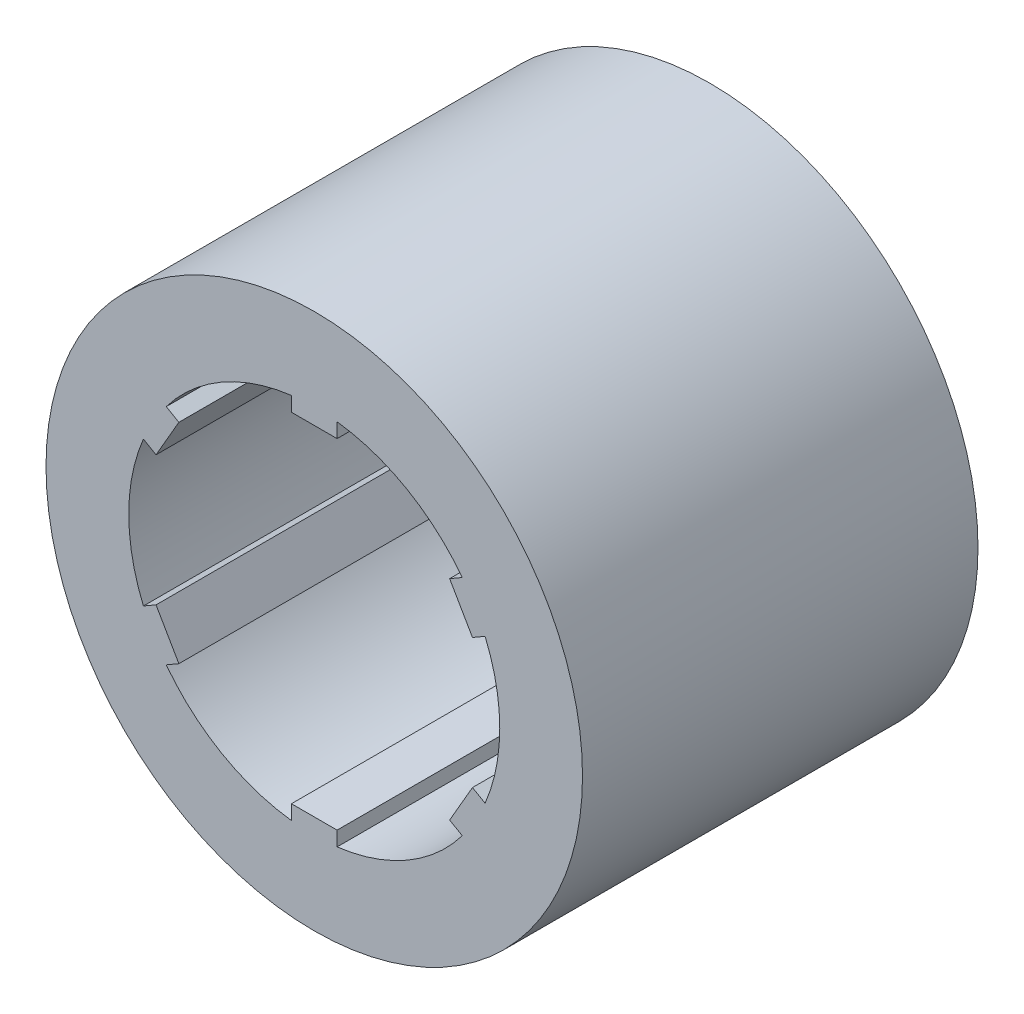
SolidWorks part; units mm, degrees
ref_plane "Спереди" through (0, 0, 0) normal (0, 0, 1) x (1, 0, 0)
ref_plane "Сверху" through (0, 0, 0) normal (0, 1, 0) x (1, 0, 0)
ref_plane "Справа" through (0, 0, 0) normal (1, 0, 0) x (0, 0, -1)
sketch "Эскиз1" plane through (0, 0, 0) normal (0, 0, 1) x (1, 0, 0)
  line L0 (9.0689, -4.0163) -> (9.7708, -4.4215)
  line L1 (9.7708, 3.6191) -> (9.0689, 3.2138)
  line L2 (9.0689, 3.2138) -> (7.7989, 5.4135)
  line L3 (7.7989, 5.4135) -> (8.5008, 5.8188)
  line L4 (1.5375, 9.8391) -> (1.5375, 9.0285)
  line L5 (1.5375, 9.0285) -> (-1.0025, 9.0285)
  line L6 (-1.0025, 9.0285) -> (-1.0025, 9.8391)
  line L7 (-7.9659, 5.8188) -> (-7.2639, 5.4135)
  line L8 (-7.2639, 5.4135) -> (-8.5339, 3.2138)
  line L9 (-8.5339, 3.2138) -> (-9.2359, 3.6191)
  line L10 (-9.2359, -4.4215) -> (-8.5339, -4.0163)
  line L11 (-8.5339, -4.0163) -> (-7.2639, -6.216)
  line L12 (-7.2639, -6.216) -> (-7.9659, -6.6212)
  line L13 (-1.0025, -10.6415) -> (-1.0025, -9.831)
  line L14 (-1.0025, -9.831) -> (1.5375, -9.831)
  line L15 (1.5375, -9.831) -> (1.5375, -10.6415)
  line L16 (8.5008, -6.6212) -> (7.7989, -6.216)
  line L17 (7.7989, -6.216) -> (9.0689, -4.0163)
  circle A0 centre (0.2675, -0.4012) radius 14.9225
  arc A1 (9.7708, -4.4215) -> (9.7708, 3.6191) centre (0.2675, -0.4012) ccw
  arc A2 (8.5008, 5.8188) -> (1.5375, 9.8391) centre (0.2675, -0.4012) ccw
  arc A3 (-1.0025, 9.8391) -> (-7.9659, 5.8188) centre (0.2675, -0.4012) ccw
  arc A4 (-9.2359, 3.6191) -> (-9.2359, -4.4215) centre (0.2675, -0.4012) ccw
  arc A5 (-7.9659, -6.6212) -> (-1.0025, -10.6415) centre (0.2675, -0.4012) ccw
  arc A6 (1.5375, -10.6415) -> (8.5008, -6.6212) centre (0.2675, -0.4012) ccw
extrude "Бобышка-Вытянуть1" add sketch "Эскиз1" along normal blind 22
